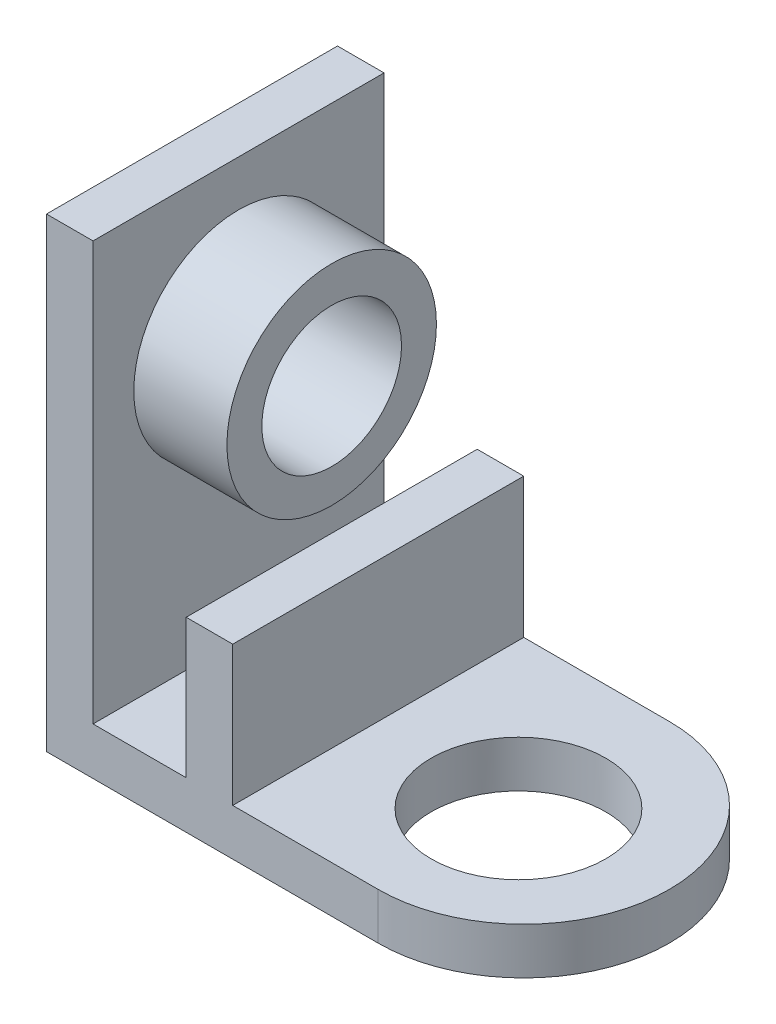
SolidWorks part; units mm, degrees
ref_plane "Ön Düzlem" through (0, 0, 0) normal (0, 0, 1) x (1, 0, 0)
ref_plane "Üst Düzlem" through (0, 0, 0) normal (0, 1, 0) x (1, 0, 0)
ref_plane "Sağ Düzlem" through (0, 0, 0) normal (1, 0, 0) x (0, 0, -1)
sketch "Çizim1" plane through (0, 0, 0) normal (0, 0, 1) x (1, 0, 0)
  line L0 (0, 2032) -> (0, 0)
  line L1 (0, 0) -> (1447.8, 0)
  line L2 (1447.8, 0) -> (1447.8, 203.2)
  line L3 (1447.8, 203.2) -> (812.8, 203.2)
  line L4 (812.8, 203.2) -> (812.8, 812.8)
  line L5 (812.8, 812.8) -> (609.6, 812.8)
  line L6 (609.6, 812.8) -> (609.6, 206.3279)
  line L7 (609.6, 206.3279) -> (203.2, 206.3279)
  line L8 (203.2, 206.3279) -> (203.2, 2032)
  line L9 (203.2, 2032) -> (0, 2032)
  dimension "D1" = 203.2
  dimension "D2" = 203.2
  dimension "D3" = 203.2
  dimension "D4" = 2032
  dimension "D5" = 609.6
  dimension "D6" = 1447.8
  dimension "D7" = 635
extrude "Yükseklik-Ekstrüzyon1" add sketch "Çizim1" along normal blind 1270
sketch "Çizim2" plane through (0, 203.2, 0) normal (0, 1, 0) x (1, 0, 0)
  line L4 (1447.8, 0) -> (812.8, 0)
  line L5 (812.8, 0) -> (812.8, -1270)
  line L6 (812.8, -1270) -> (1447.8, -1270)
  line L7 (1447.8, -1270) -> (1447.8, 0)
  line L11 (1447.8, -1270) -> (1447.8, 0)
  arc A0 (1447.8, 0) -> (1447.8, -1270) centre (1447.8, -635) cw
  dimension "D1" = 635
  dimension "D2" = 0
extrude "Yükseklik-Ekstrüzyon2" add sketch "Çizim2" against normal blind 203.2
sketch "Çizim3" plane through (0, 203.2, 0) normal (0, 1, 0) x (1, 0, 0)
  line L0 (812.8, -1270) -> (812.8, 0) construction
  circle A0 centre (1447.8, -658.0826) radius 381
  dimension "D1" = 762
  dimension "D2" = 635
extrude "Kes-Ekstrüzyon1" cut sketch "Çizim3" against normal through all both and the other way through all
sketch "Çizim4" plane through (203.2, 0, 0) normal (1, 0, 0) x (0, 0, -1)
  line L0 (-1270, 206.3279) -> (0, 206.3279) construction
  line L1 (-1270, 206.3279) -> (-1270, 2032) construction
  circle A0 centre (-635, 1374.7279) radius 457.2
  dimension "D1" = 1168.4
  dimension "D2" = 914.4
  dimension "D3" = 635
extrude "Yükseklik-Ekstrüzyon3" add sketch "Çizim4" along normal blind 406.4
sketch "Çizim5" plane through (609.6, 0, 0) normal (1, 0, 0) x (0, 0, -1)
  line L0 (-1270, 206.3279) -> (-1270, 2032) construction
  circle A0 centre (-635, 1369.5174) radius 304.8
  point P4 (0, 0)
  point P7 (0, 0)
  dimension "D1" = 609.6
  dimension "D2" = 635
extrude "Kes-Ekstrüzyon2" cut sketch "Çizim5" against normal through all both and the other way through all contours A0
